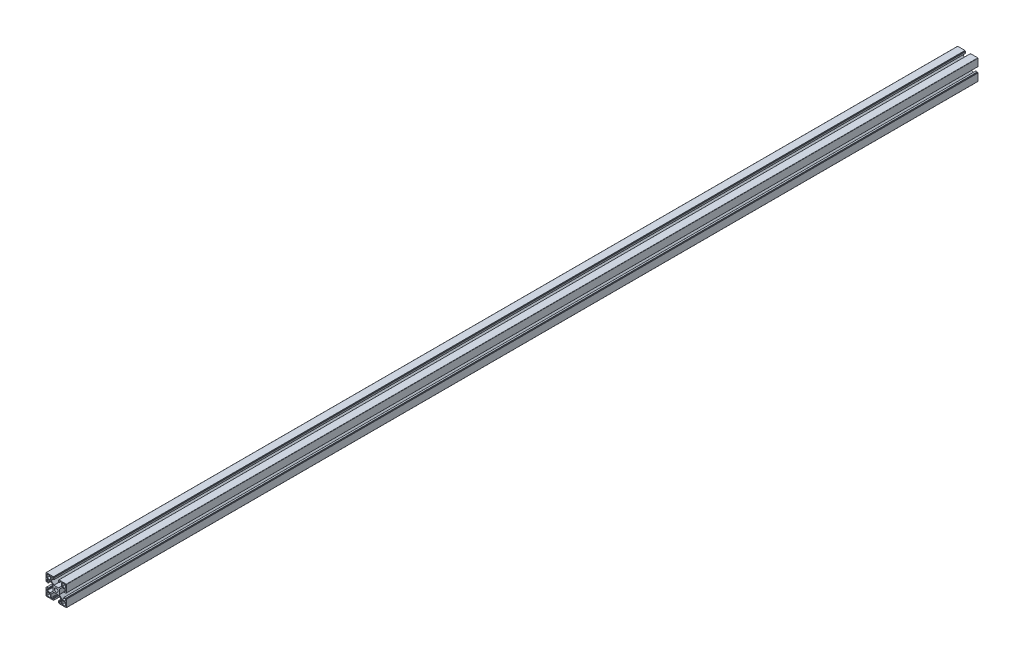
SolidWorks part; units mm, degrees
ref_plane "前视基准面" through (0, 0, 0) normal (0, 0, 1) x (1, 0, 0)
ref_plane "上视基准面" through (0, 0, 0) normal (0, 1, 0) x (1, 0, 0)
ref_plane "右视基准面" through (0, 0, 0) normal (1, 0, 0) x (0, 0, -1)
sketch "草图1" plane through (0, 0, 0) normal (0, 0, 1) x (1, 0, 0)
  line L0 (3522.7957, 265.1687) -> (3522.7957, 259.1687)
  line L1 (3522.2957, 258.6687) -> (3516.2957, 258.6687)
  line L2 (3515.7957, 259.1687) -> (3515.7957, 265.1687)
  line L3 (3516.2957, 265.6687) -> (3522.2957, 265.6687)
  line L4 (3522.2957, 288.6687) -> (3516.2957, 288.6687)
  line L5 (3515.7957, 289.1687) -> (3515.7957, 295.1687)
  line L6 (3516.2957, 295.6687) -> (3522.2957, 295.6687)
  line L7 (3522.7957, 295.1687) -> (3522.7957, 289.1687)
  line L8 (3545.7957, 289.1687) -> (3545.7957, 295.1687)
  line L9 (3546.2957, 295.6687) -> (3552.2957, 295.6687)
  line L10 (3552.7957, 295.1687) -> (3552.7957, 289.1687)
  line L11 (3552.2957, 288.6687) -> (3546.2957, 288.6687)
  line L12 (3546.2957, 265.6687) -> (3552.2957, 265.6687)
  line L13 (3552.7957, 265.1687) -> (3552.7957, 259.1687)
  line L14 (3552.2957, 258.6687) -> (3546.2957, 258.6687)
  line L15 (3545.7957, 259.1687) -> (3545.7957, 265.1687)
  line L16 (3539.028, 271.0223) -> (3544.1493, 265.901)
  line L17 (3544.2957, 265.5474) -> (3544.2957, 259.4687)
  line L18 (3543.7957, 258.9687) -> (3540.9957, 258.9687)
  line L19 (3540.4957, 259.4687) -> (3540.4957, 261.3687)
  line L20 (3540.1957, 261.6687) -> (3538.6957, 261.6687)
  line L21 (3538.3957, 261.3687) -> (3538.3957, 258.4687)
  line L22 (3538.6957, 258.1687) -> (3539.1957, 258.1687)
  line L23 (3539.3957, 257.9687) -> (3539.3957, 257.4687)
  line L24 (3539.6957, 257.1687) -> (3553.7957, 257.1687)
  line L25 (3554.2957, 257.6687) -> (3554.2957, 271.7687)
  line L26 (3553.9957, 272.0687) -> (3553.4957, 272.0687)
  line L27 (3553.2957, 272.2687) -> (3553.2957, 272.7687)
  line L28 (3552.9957, 273.0687) -> (3550.0957, 273.0687)
  line L29 (3549.7957, 272.7687) -> (3549.7957, 271.2687)
  line L30 (3550.0957, 270.9687) -> (3551.9957, 270.9687)
  line L31 (3552.4957, 270.4687) -> (3552.4957, 267.6687)
  line L32 (3551.9957, 267.1687) -> (3545.9171, 267.1687)
  line L33 (3545.5635, 267.3152) -> (3540.4422, 272.4365)
  line L34 (3540.2957, 272.7901) -> (3540.2957, 281.5474)
  line L35 (3540.4422, 281.901) -> (3545.5635, 287.0223)
  line L36 (3545.9171, 287.1687) -> (3551.9957, 287.1687)
  line L37 (3552.4957, 286.6687) -> (3552.4957, 283.8687)
  line L38 (3551.9957, 283.3687) -> (3550.0957, 283.3687)
  line L39 (3549.7957, 283.0687) -> (3549.7957, 281.5687)
  line L40 (3550.0957, 281.2687) -> (3552.9957, 281.2687)
  line L41 (3553.2957, 281.5687) -> (3553.2957, 282.0687)
  line L42 (3553.4957, 282.2687) -> (3553.9957, 282.2687)
  line L43 (3554.2957, 282.5687) -> (3554.2957, 296.6687)
  line L44 (3553.7957, 297.1687) -> (3539.6957, 297.1687)
  line L45 (3539.3957, 296.8687) -> (3539.3957, 296.3687)
  line L46 (3539.1957, 296.1687) -> (3538.6957, 296.1687)
  line L47 (3538.3957, 295.8687) -> (3538.3957, 292.9687)
  line L48 (3538.6957, 292.6687) -> (3540.1957, 292.6687)
  line L49 (3540.4957, 292.9687) -> (3540.4957, 294.8687)
  line L50 (3540.9957, 295.3687) -> (3543.7957, 295.3687)
  line L51 (3544.2957, 294.8687) -> (3544.2957, 288.7901)
  line L52 (3544.1493, 288.4365) -> (3539.028, 283.3152)
  line L53 (3538.6744, 283.1687) -> (3529.9171, 283.1687)
  line L54 (3529.5635, 283.3152) -> (3524.4422, 288.4365)
  line L55 (3524.2957, 288.7901) -> (3524.2957, 294.8687)
  line L56 (3524.7957, 295.3687) -> (3527.5957, 295.3687)
  line L57 (3528.0957, 294.8687) -> (3528.0957, 292.9687)
  line L58 (3528.3957, 292.6687) -> (3529.8957, 292.6687)
  line L59 (3530.1957, 292.9687) -> (3530.1957, 295.8687)
  line L60 (3529.8957, 296.1687) -> (3529.3957, 296.1687)
  line L61 (3529.1957, 296.3687) -> (3529.1957, 296.8687)
  line L62 (3528.8957, 297.1687) -> (3514.7957, 297.1687)
  line L63 (3514.2957, 296.6687) -> (3514.2957, 282.5687)
  line L64 (3514.5957, 282.2687) -> (3515.0957, 282.2687)
  line L65 (3515.2957, 282.0687) -> (3515.2957, 281.5687)
  line L66 (3515.5957, 281.2687) -> (3518.4957, 281.2687)
  line L67 (3518.7957, 281.5687) -> (3518.7957, 283.0687)
  line L68 (3518.4957, 283.3687) -> (3516.5957, 283.3687)
  line L69 (3516.0957, 283.8687) -> (3516.0957, 286.6687)
  line L70 (3516.5957, 287.1687) -> (3522.6744, 287.1687)
  line L71 (3523.028, 287.0223) -> (3528.1493, 281.901)
  line L72 (3528.2957, 281.5474) -> (3528.2957, 272.7901)
  line L73 (3528.1493, 272.4365) -> (3523.028, 267.3152)
  line L74 (3522.6744, 267.1687) -> (3516.5957, 267.1687)
  line L75 (3516.0957, 267.6687) -> (3516.0957, 270.4687)
  line L76 (3516.5957, 270.9687) -> (3518.4957, 270.9687)
  line L77 (3518.7957, 271.2687) -> (3518.7957, 272.7687)
  line L78 (3518.4957, 273.0687) -> (3515.5957, 273.0687)
  line L79 (3515.2957, 272.7687) -> (3515.2957, 272.2687)
  line L80 (3515.0957, 272.0687) -> (3514.5957, 272.0687)
  line L81 (3514.2957, 271.7687) -> (3514.2957, 257.6687)
  line L82 (3514.7957, 257.1687) -> (3528.8957, 257.1687)
  line L83 (3529.1957, 257.4687) -> (3529.1957, 257.9687)
  line L84 (3529.3957, 258.1687) -> (3529.8957, 258.1687)
  line L85 (3530.1957, 258.4687) -> (3530.1957, 261.3687)
  line L86 (3529.8957, 261.6687) -> (3528.3957, 261.6687)
  line L87 (3528.0957, 261.3687) -> (3528.0957, 259.4687)
  line L88 (3527.5957, 258.9687) -> (3524.7957, 258.9687)
  line L89 (3524.2957, 259.4687) -> (3524.2957, 265.5474)
  line L90 (3524.4422, 265.901) -> (3529.5635, 271.0223)
  line L91 (3529.9171, 271.1687) -> (3538.6744, 271.1687)
  arc A0 (3522.7957, 265.1687) -> (3522.2957, 265.6687) centre (3522.2957, 265.1687) ccw
  arc A1 (3522.2957, 258.6687) -> (3522.7957, 259.1687) centre (3522.2957, 259.1687) ccw
  arc A2 (3515.7957, 259.1687) -> (3516.2957, 258.6687) centre (3516.2957, 259.1687) ccw
  arc A3 (3516.2957, 265.6687) -> (3515.7957, 265.1687) centre (3516.2957, 265.1687) ccw
  arc A4 (3522.2957, 288.6687) -> (3522.7957, 289.1687) centre (3522.2957, 289.1687) ccw
  arc A5 (3515.7957, 289.1687) -> (3516.2957, 288.6687) centre (3516.2957, 289.1687) ccw
  arc A6 (3516.2957, 295.6687) -> (3515.7957, 295.1687) centre (3516.2957, 295.1687) ccw
  arc A7 (3522.7957, 295.1687) -> (3522.2957, 295.6687) centre (3522.2957, 295.1687) ccw
  arc A8 (3545.7957, 289.1687) -> (3546.2957, 288.6687) centre (3546.2957, 289.1687) ccw
  arc A9 (3546.2957, 295.6687) -> (3545.7957, 295.1687) centre (3546.2957, 295.1687) ccw
  arc A10 (3552.7957, 295.1687) -> (3552.2957, 295.6687) centre (3552.2957, 295.1687) ccw
  arc A11 (3552.2957, 288.6687) -> (3552.7957, 289.1687) centre (3552.2957, 289.1687) ccw
  circle A12 centre (3534.2957, 277.1687) radius 3.4
  arc A13 (3546.2957, 265.6687) -> (3545.7957, 265.1687) centre (3546.2957, 265.1687) ccw
  arc A14 (3552.7957, 265.1687) -> (3552.2957, 265.6687) centre (3552.2957, 265.1687) ccw
  arc A15 (3552.2957, 258.6687) -> (3552.7957, 259.1687) centre (3552.2957, 259.1687) ccw
  arc A16 (3545.7957, 259.1687) -> (3546.2957, 258.6687) centre (3546.2957, 259.1687) ccw
  arc A17 (3544.2957, 265.5474) -> (3544.1493, 265.901) centre (3543.7957, 265.5474) ccw
  arc A18 (3543.7957, 258.9687) -> (3544.2957, 259.4687) centre (3543.7957, 259.4687) ccw
  arc A19 (3540.4957, 259.4687) -> (3540.9957, 258.9687) centre (3540.9957, 259.4687) ccw
  arc A20 (3540.4957, 261.3687) -> (3540.1957, 261.6687) centre (3540.1957, 261.3687) ccw
  arc A21 (3538.6957, 261.6687) -> (3538.3957, 261.3687) centre (3538.6957, 261.3687) ccw
  arc A22 (3538.3957, 258.4687) -> (3538.6957, 258.1687) centre (3538.6957, 258.4687) ccw
  arc A23 (3539.3957, 257.9687) -> (3539.1957, 258.1687) centre (3539.1957, 257.9687) ccw
  arc A24 (3539.3957, 257.4687) -> (3539.6957, 257.1687) centre (3539.6957, 257.4687) ccw
  arc A25 (3553.7957, 257.1687) -> (3554.2957, 257.6687) centre (3553.7957, 257.6687) ccw
  arc A26 (3554.2957, 271.7687) -> (3553.9957, 272.0687) centre (3553.9957, 271.7687) ccw
  arc A27 (3553.2957, 272.2687) -> (3553.4957, 272.0687) centre (3553.4957, 272.2687) ccw
  arc A28 (3553.2957, 272.7687) -> (3552.9957, 273.0687) centre (3552.9957, 272.7687) ccw
  arc A29 (3550.0957, 273.0687) -> (3549.7957, 272.7687) centre (3550.0957, 272.7687) ccw
  arc A30 (3549.7957, 271.2687) -> (3550.0957, 270.9687) centre (3550.0957, 271.2687) ccw
  arc A31 (3552.4957, 270.4687) -> (3551.9957, 270.9687) centre (3551.9957, 270.4687) ccw
  arc A32 (3551.9957, 267.1687) -> (3552.4957, 267.6687) centre (3551.9957, 267.6687) ccw
  arc A33 (3545.5635, 267.3152) -> (3545.9171, 267.1687) centre (3545.9171, 267.6687) ccw
  arc A34 (3540.2957, 272.7901) -> (3540.4422, 272.4365) centre (3540.7957, 272.7901) ccw
  arc A35 (3540.4422, 281.901) -> (3540.2957, 281.5474) centre (3540.7957, 281.5474) ccw
  arc A36 (3545.9171, 287.1687) -> (3545.5635, 287.0223) centre (3545.9171, 286.6687) ccw
  arc A37 (3552.4957, 286.6687) -> (3551.9957, 287.1687) centre (3551.9957, 286.6687) ccw
  arc A38 (3551.9957, 283.3687) -> (3552.4957, 283.8687) centre (3551.9957, 283.8687) ccw
  arc A39 (3550.0957, 283.3687) -> (3549.7957, 283.0687) centre (3550.0957, 283.0687) ccw
  arc A40 (3549.7957, 281.5687) -> (3550.0957, 281.2687) centre (3550.0957, 281.5687) ccw
  arc A41 (3552.9957, 281.2687) -> (3553.2957, 281.5687) centre (3552.9957, 281.5687) ccw
  arc A42 (3553.4957, 282.2687) -> (3553.2957, 282.0687) centre (3553.4957, 282.0687) ccw
  arc A43 (3553.9957, 282.2687) -> (3554.2957, 282.5687) centre (3553.9957, 282.5687) ccw
  arc A44 (3554.2957, 296.6687) -> (3553.7957, 297.1687) centre (3553.7957, 296.6687) ccw
  arc A45 (3539.6957, 297.1687) -> (3539.3957, 296.8687) centre (3539.6957, 296.8687) ccw
  arc A46 (3539.1957, 296.1687) -> (3539.3957, 296.3687) centre (3539.1957, 296.3687) ccw
  arc A47 (3538.6957, 296.1687) -> (3538.3957, 295.8687) centre (3538.6957, 295.8687) ccw
  arc A48 (3538.3957, 292.9687) -> (3538.6957, 292.6687) centre (3538.6957, 292.9687) ccw
  arc A49 (3540.1957, 292.6687) -> (3540.4957, 292.9687) centre (3540.1957, 292.9687) ccw
  arc A50 (3540.9957, 295.3687) -> (3540.4957, 294.8687) centre (3540.9957, 294.8687) ccw
  arc A51 (3544.2957, 294.8687) -> (3543.7957, 295.3687) centre (3543.7957, 294.8687) ccw
  arc A52 (3544.1493, 288.4365) -> (3544.2957, 288.7901) centre (3543.7957, 288.7901) ccw
  arc A53 (3538.6744, 283.1687) -> (3539.028, 283.3152) centre (3538.6744, 283.6687) ccw
  arc A54 (3529.5635, 283.3152) -> (3529.9171, 283.1687) centre (3529.9171, 283.6687) ccw
  arc A55 (3524.2957, 288.7901) -> (3524.4422, 288.4365) centre (3524.7957, 288.7901) ccw
  arc A56 (3524.7957, 295.3687) -> (3524.2957, 294.8687) centre (3524.7957, 294.8687) ccw
  arc A57 (3528.0957, 294.8687) -> (3527.5957, 295.3687) centre (3527.5957, 294.8687) ccw
  arc A58 (3528.0957, 292.9687) -> (3528.3957, 292.6687) centre (3528.3957, 292.9687) ccw
  arc A59 (3529.8957, 292.6687) -> (3530.1957, 292.9687) centre (3529.8957, 292.9687) ccw
  arc A60 (3530.1957, 295.8687) -> (3529.8957, 296.1687) centre (3529.8957, 295.8687) ccw
  arc A61 (3529.1957, 296.3687) -> (3529.3957, 296.1687) centre (3529.3957, 296.3687) ccw
  arc A62 (3529.1957, 296.8687) -> (3528.8957, 297.1687) centre (3528.8957, 296.8687) ccw
  arc A63 (3514.7957, 297.1687) -> (3514.2957, 296.6687) centre (3514.7957, 296.6687) ccw
  arc A64 (3514.2957, 282.5687) -> (3514.5957, 282.2687) centre (3514.5957, 282.5687) ccw
  arc A65 (3515.2957, 282.0687) -> (3515.0957, 282.2687) centre (3515.0957, 282.0687) ccw
  arc A66 (3515.2957, 281.5687) -> (3515.5957, 281.2687) centre (3515.5957, 281.5687) ccw
  arc A67 (3518.4957, 281.2687) -> (3518.7957, 281.5687) centre (3518.4957, 281.5687) ccw
  arc A68 (3518.7957, 283.0687) -> (3518.4957, 283.3687) centre (3518.4957, 283.0687) ccw
  arc A69 (3516.0957, 283.8687) -> (3516.5957, 283.3687) centre (3516.5957, 283.8687) ccw
  arc A70 (3516.5957, 287.1687) -> (3516.0957, 286.6687) centre (3516.5957, 286.6687) ccw
  arc A71 (3523.028, 287.0223) -> (3522.6744, 287.1687) centre (3522.6744, 286.6687) ccw
  arc A72 (3528.2957, 281.5474) -> (3528.1493, 281.901) centre (3527.7957, 281.5474) ccw
  arc A73 (3528.1493, 272.4365) -> (3528.2957, 272.7901) centre (3527.7957, 272.7901) ccw
  arc A74 (3522.6744, 267.1687) -> (3523.028, 267.3152) centre (3522.6744, 267.6687) ccw
  arc A75 (3516.0957, 267.6687) -> (3516.5957, 267.1687) centre (3516.5957, 267.6687) ccw
  arc A76 (3516.5957, 270.9687) -> (3516.0957, 270.4687) centre (3516.5957, 270.4687) ccw
  arc A77 (3518.4957, 270.9687) -> (3518.7957, 271.2687) centre (3518.4957, 271.2687) ccw
  arc A78 (3518.7957, 272.7687) -> (3518.4957, 273.0687) centre (3518.4957, 272.7687) ccw
  arc A79 (3515.5957, 273.0687) -> (3515.2957, 272.7687) centre (3515.5957, 272.7687) ccw
  arc A80 (3515.0957, 272.0687) -> (3515.2957, 272.2687) centre (3515.0957, 272.2687) ccw
  arc A81 (3514.5957, 272.0687) -> (3514.2957, 271.7687) centre (3514.5957, 271.7687) ccw
  arc A82 (3514.2957, 257.6687) -> (3514.7957, 257.1687) centre (3514.7957, 257.6687) ccw
  arc A83 (3528.8957, 257.1687) -> (3529.1957, 257.4687) centre (3528.8957, 257.4687) ccw
  arc A84 (3529.3957, 258.1687) -> (3529.1957, 257.9687) centre (3529.3957, 257.9687) ccw
  arc A85 (3529.8957, 258.1687) -> (3530.1957, 258.4687) centre (3529.8957, 258.4687) ccw
  arc A86 (3530.1957, 261.3687) -> (3529.8957, 261.6687) centre (3529.8957, 261.3687) ccw
  arc A87 (3528.3957, 261.6687) -> (3528.0957, 261.3687) centre (3528.3957, 261.3687) ccw
  arc A88 (3527.5957, 258.9687) -> (3528.0957, 259.4687) centre (3527.5957, 259.4687) ccw
  arc A89 (3524.2957, 259.4687) -> (3524.7957, 258.9687) centre (3524.7957, 259.4687) ccw
  arc A90 (3524.4422, 265.901) -> (3524.2957, 265.5474) centre (3524.7957, 265.5474) ccw
  arc A91 (3529.9171, 271.1687) -> (3529.5635, 271.0223) centre (3529.9171, 270.6687) ccw
  arc A92 (3539.028, 271.0223) -> (3538.6744, 271.1687) centre (3538.6744, 270.6687) ccw
  dimension "D1" = 6.8
extrude "凸台-拉伸1" add sketch "草图1" along normal up to surface (1780 mm away)
